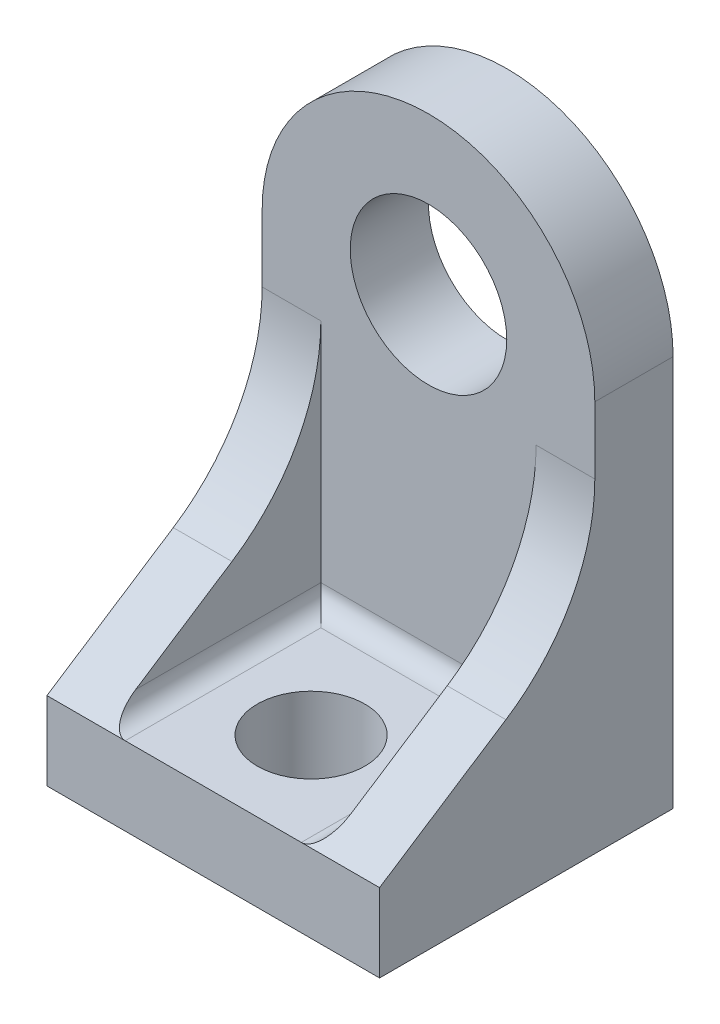
SolidWorks part; units mm, degrees
ref_plane "Plano frontal" through (0, 0, 0) normal (0, 0, 1) x (1, 0, 0)
ref_plane "Plano superior" through (0, 0, 0) normal (0, 1, 0) x (1, 0, 0)
ref_plane "Plano direito" through (0, 0, 0) normal (1, 0, 0) x (0, 0, -1)
sketch "Esboço1" plane through (0, 0, 0) normal (0, 0, 1) x (1, 0, 0)
  line L1 (-8.5, 0) -> (8.5, 0)
  line L2 (-8.5, 0) -> (-8.5, 20)
  line L4 (8.5, 0) -> (8.5, 20)
  arc A0 (-8.5, 20) -> (8.5, 20) centre (0, 20) cw
  point P4 (0, 0)
  dimension "D2" = 8.5
  dimension "D1" = 20
extrude "Ressalto-extrusão1" add sketch "Esboço1" along normal blind 15
sketch "Esboço2" plane through (0, 0, 15) normal (0, 0, 1) x (1, 0, 0)
  line L0 (-5.5, 4) -> (5.5, 4)
  line L1 (5.5, 4) -> (5.5, 26.4807)
  line L4 (-5.5, 26.4807) -> (-5.5, 4)
  line L5 (-8.5, 0) -> (8.5, 0) construction
  line L6 (8.5, 0) -> (8.5, 20) construction
  arc A0 (-5.5, 26.4807) -> (5.5, 26.4807) centre (0, 20) cw
  arc A1 (8.5, 20) -> (-8.5, 20) centre (0, 20) ccw construction
  point P5 (0, 4)
  dimension "D1" = 4
  dimension "D2" = 3
extrude "Corte-extrusão1" cut sketch "Esboço2" against normal blind 11
sketch "Esboço3" plane through (8.5, 0, 0) normal (1, 0, 0) x (0, 0, -1)
  line L0 (-15, 4) -> (-4, 11.1632)
  line L1 (-15, 0) -> (-15, 20) construction
  line L2 (-4, 11.1632) -> (-4, 28.5)
  line L4 (-4, 28.5) -> (-15, 28.5)
  line L5 (-15, 28.5) -> (-15, 4)
  line L6 (-15, 0) -> (0, 0) construction
  line L7 (0, 0) -> (0, 20) construction
  line L8 (0, 28.5) -> (-4, 28.5) construction
  dimension "D1" = 4
  dimension "D2" = 4
  dimension "D3" = 56.928
extrude "Corte-extrusão2" cut sketch "Esboço3" against normal through all
fillet "Filete1" radius 10 2 edges at (-7, 11.1632, 4) (7, 11.1632, 4)
fillet "Filete2" radius 1 3 edges at (-5.5, 4, 9.5) (5.5, 4, 9.5) (0, 4, 4)
sketch "Esboço4" plane through (0, 4, 0) normal (0, 1, 0) x (1, 0, 0)
  line L0 (-4.5, -10) -> (4.5, -10) construction
  line L1 (-4.5, -5) -> (-4.5, -15) construction
  line L2 (4.5, -15) -> (4.5, -5) construction
  line L3 (0, -15) -> (0, -5) construction
  line L4 (-4.5, -15) -> (4.5, -15) construction
  line L5 (4.5, -5) -> (-4.5, -5) construction
hole_wizard "Furo com folga de M51" positions "Esboço5" profile "Esboço6" hole size "M5" standard "Ansi Metric" end condition through all
sketch "Esboço5" plane through (0, 4, 0) normal (0, 1, 0) x (1, 0, 0)
  line L0 (-4.5, -10) -> (4.5, -10) construction
  point P0 (0, -10)
sketch "Esboço6" plane through (0, 4, 10) normal (1, 0, 0) x (0, 0, 1)
  line L0 (0, 0) -> (0, 4)
  line L1 (0, 4) -> (2.75, 4)
  line L2 (2.75, 4) -> (2.75, 0)
  line L5 (2.75, 0) -> (0, 0)
  line L11 (0, -6.35) -> (0, 107.95) construction
  dimension "Thru Hole Dia." = 5.5
  dimension "Thru Hole Depth" = 4
sketch "Esboço7" plane through (0, 0, 4) normal (0, 0, 1) x (1, 0, 0)
  line L0 (0, 28.5) -> (0, 20.5) construction
  circle A0 centre (0, 20.5) radius 4
  arc A1 (8.5, 20) -> (-8.5, 20) centre (0, 20) ccw construction
  dimension "D2" = 8
  dimension "D1" = 8
extrude "Corte-extrusão3" cut sketch "Esboço7" against normal through all
